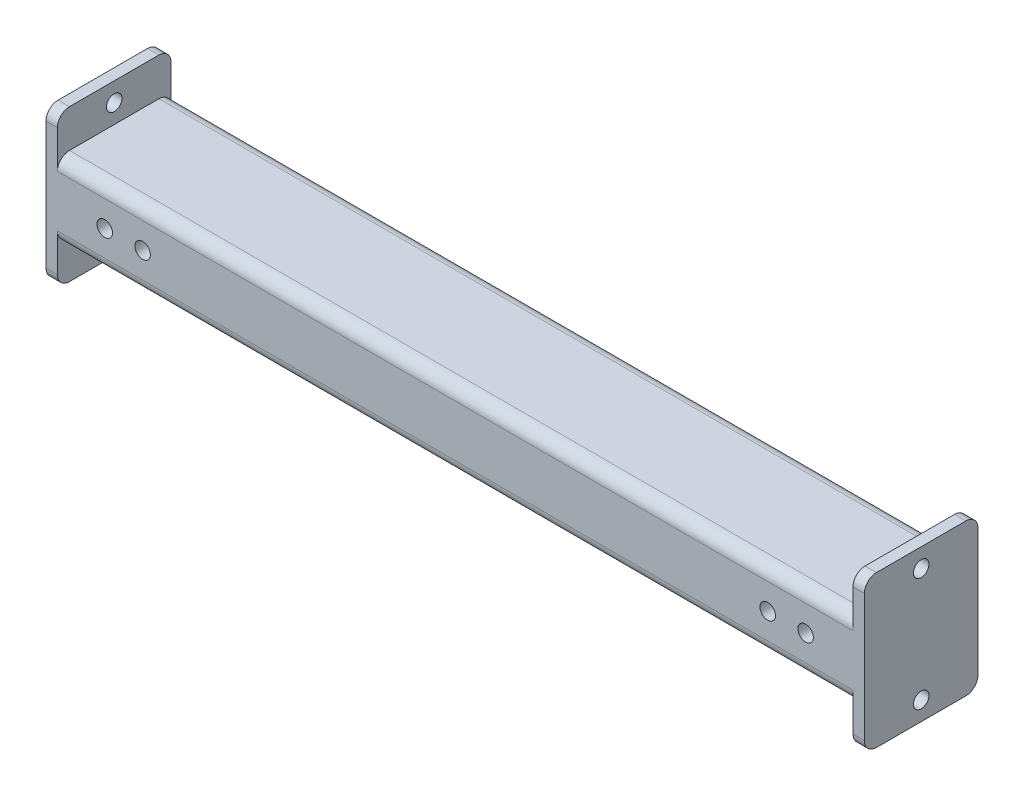
SolidWorks part; units mm, degrees
ref_plane "Płaszczyzna przednia" through (0, 0, 0) normal (0, 0, 1) x (1, 0, 0)
ref_plane "Płaszczyzna górna" through (0, 0, 0) normal (0, 1, 0) x (1, 0, 0)
ref_plane "Płaszczyzna prawa" through (0, 0, 0) normal (1, 0, 0) x (0, 0, -1)
sketch "Szkic3" plane through (0, 0, 0) normal (1, 0, 0) x (0, 0, -1)
  line L0 (-17.6, 14) -> (17.6, 14)
  line L1 (-23.6, -20) -> (23.6, -20)
  line L2 (-30, -13.6) -> (-30, 13.6)
  line L3 (-23.6, 20) -> (23.6, 20)
  line L4 (30, -13.6) -> (30, 13.6)
  line L5 (-30, -20) -> (30, 20) construction
  line L6 (-30, 20) -> (30, -20) construction
  line L7 (24, -7.6) -> (24, 7.6)
  line L8 (-17.6, -14) -> (17.6, -14)
  line L9 (-24, -7.6) -> (-24, 7.6)
  line L10 (-24, -14) -> (24, -14) construction
  line L11 (-24, -14) -> (-24, 14) construction
  line L12 (24, -14) -> (24, 14) construction
  line L13 (-24, 14) -> (24, 14) construction
  line L14 (-30, -20) -> (30, -20) construction
  line L15 (30, -20) -> (30, 20) construction
  line L16 (-30, -20) -> (-30, 20) construction
  line L17 (-30, 20) -> (30, 20) construction
  arc A0 (-17.6, -14) -> (-24, -7.6) centre (-17.6, -7.6) cw
  arc A1 (24, -7.6) -> (17.6, -14) centre (17.6, -7.6) cw
  arc A2 (17.6, 14) -> (24, 7.6) centre (17.6, 7.6) cw
  arc A3 (-17.6, 14) -> (-24, 7.6) centre (-17.6, 7.6) ccw
  arc A4 (23.6, -20) -> (30, -13.6) centre (23.6, -13.6) ccw
  arc A5 (-23.6, -20) -> (-30, -13.6) centre (-23.6, -13.6) cw
  arc A6 (-30, 13.6) -> (-23.6, 20) centre (-23.6, 13.6) cw
  arc A7 (23.6, 20) -> (30, 13.6) centre (23.6, 13.6) cw
  point P0 (0, 0)
  dimension "D4" = 6.4
  dimension "D5" = 6.4
  dimension "D1" = 60
  dimension "D2" = 40
  dimension "D3" = 6
extrude "Dodanie-wyciągnięcie2" add sketch "Szkic3" along normal blind 420
sketch "Szkic4" plane through (420, 0, 0) normal (1, 0, 0) x (0, 0, -1)
  line L0 (55, 0) -> (-55, 0) construction
  line L1 (-23.6, -40) -> (23.6, -40)
  line L2 (-30, -33.6) -> (-30, 33.6)
  line L3 (-23.6, 40) -> (23.6, 40)
  line L4 (30, -33.6) -> (30, 33.6)
  line L5 (-30, -40) -> (30, 40) construction
  line L6 (-30, 40) -> (30, -40) construction
  line L7 (0, 55) -> (0, -55) construction
  circle A0 centre (0, 30) radius 4.1
  circle A1 centre (0, -30) radius 4.1
  arc A2 (23.6, -40) -> (30, -33.6) centre (23.6, -33.6) ccw
  arc A3 (23.6, 40) -> (30, 33.6) centre (23.6, 33.6) cw
  arc A4 (-30, 33.6) -> (-23.6, 40) centre (-23.6, 33.6) cw
  arc A5 (-23.6, -40) -> (-30, -33.6) centre (-23.6, -33.6) cw
  point P0 (0, 0)
  dimension "D3" = 8.2
  dimension "D5" = 6.4
  dimension "D1" = 60
  dimension "D2" = 80
  dimension "D4" = 30
extrude "Dodanie-wyciągnięcie3" add sketch "Szkic4" along normal blind 6
ref_plane "Płaszczyzna1" through (210, 0, 0) normal (1, 0, 0) x (0, 0, -1)
sketch "Szkic5" plane through (0, 0, 30) normal (0, 0, 1) x (1, 0, 0)
  line L0 (33, 0) -> (-33, 0) construction
  line L1 (0, -33) -> (0, 33) construction
  circle A0 centre (25, 0) radius 4.1
  circle A1 centre (25, 0) radius 8.1
  circle A3 centre (45, 0) radius 4.1
  circle A4 centre (45, 0) radius 8.1
  dimension "D1" = 8.2
  dimension "D2" = 16.2
  dimension "D3" = 8.2
  dimension "D4" = 16.2
  dimension "D5" = 25
  dimension "D6" = 20
extrude "Dodanie-wyciągnięcie4" add sketch "Szkic5" against normal through all
sketch "Szkic6" plane through (0, 0, 30) normal (0, 0, 1) x (1, 0, 0)
  circle A0 centre (25, 0) radius 4.1
  circle A1 centre (45, 0) radius 4.1
extrude "Wytnij-wyciągnięcie1" cut sketch "Szkic6" against normal through all
mirror "Lustro3" about plane through (210, 0, 0) normal (1, 0, 0) of "Dodanie-wyciągnięcie4", "Wytnij-wyciągnięcie1"
mirror "Lustro4" about plane through (210, 0, 0) normal (1, 0, 0) of "Dodanie-wyciągnięcie3"
